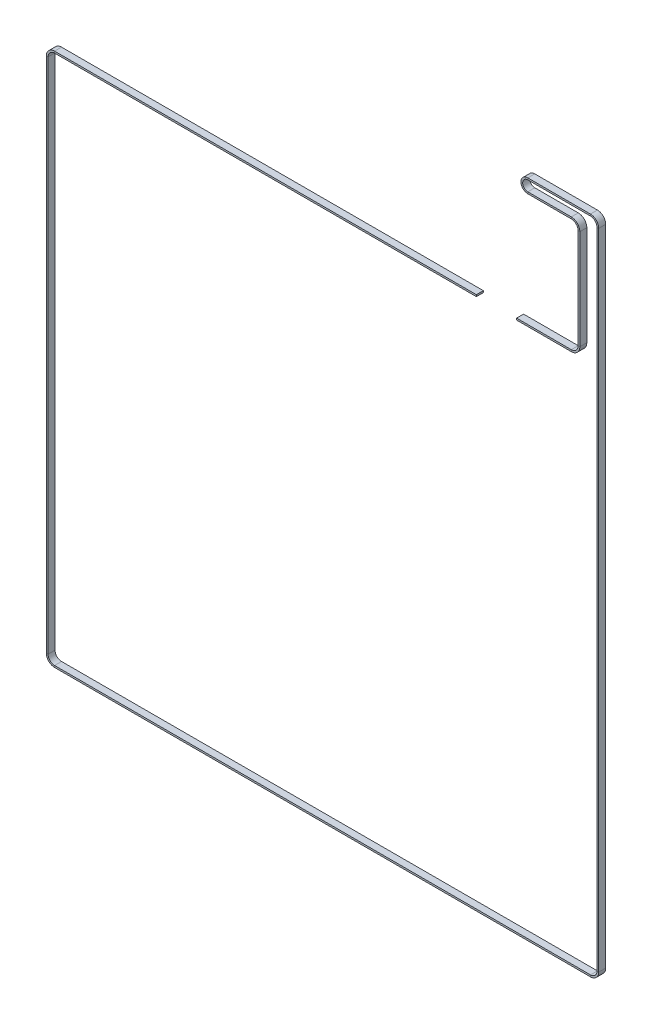
SolidWorks part; units mm, degrees
ref_plane "Front" through (0, 0, 0) normal (0, 0, 1) x (1, 0, 0)
ref_plane "Top" through (0, 0, 0) normal (0, 1, 0) x (1, 0, 0)
ref_plane "Right" through (0, 0, 0) normal (1, 0, 0) x (0, 0, -1)
sketch "Sketch1" plane through (0, 0, 2.2) normal (0, 0, 1) x (1, 0, 0)
  line L0 (377.3122, -142.2854) -> (431.3122, -142.2854)
  line L1 (377.3122, -152.6854) -> (414.8122, -152.6854)
  line L2 (421.4122, -159.2854) -> (421.4122, -245.207)
  line L3 (437.6872, -148.6604) -> (437.6872, -703.9854)
  line L4 (-37.0628, -703.9854) -> (-37.0628, -258.032)
  line L5 (431.3122, -710.3604) -> (-30.6878, -710.3604)
  line L6 (-30.6878, -251.657) -> (332.9622, -251.657)
  line L8 (367.6622, -251.707) -> (367.6622, -255.207) construction
  line L9 (414.8122, -251.807) -> (367.6622, -251.807)
  line L11 (332.9622, -251.707) -> (332.9622, -255.207) construction
  circle A0 centre (414.8122, -159.2854) radius 6.6 construction
  circle A1 centre (431.3122, -148.6604) radius 6.375 construction
  circle A2 centre (377.3122, -147.4854) radius 5.2 construction
  arc A3 (431.3122, -142.2854) -> (437.6872, -148.6604) centre (431.3122, -148.6604) cw
  arc A4 (377.3122, -152.6854) -> (377.3122, -142.2854) centre (377.3122, -147.4854) cw
  arc A5 (414.8122, -152.6854) -> (421.4122, -159.2854) centre (414.8122, -159.2854) cw
  circle A6 centre (-30.6878, -703.9854) radius 6.375 construction
  arc A7 (-30.6878, -710.3604) -> (-37.0628, -703.9854) centre (-30.6878, -703.9854) cw
  circle A8 centre (431.3122, -148.6604) radius 9 construction
  circle A9 centre (414.8122, -159.2854) radius 9 construction
  circle A10 centre (-30.6878, -258.032) radius 6.375 construction
  circle A11 centre (431.3122, -703.9854) radius 6.375 construction
  arc A12 (437.6872, -703.9854) -> (431.3122, -710.3604) centre (431.3122, -703.9854) cw
  arc A13 (-37.0628, -258.032) -> (-30.6878, -251.657) centre (-30.6878, -258.032) cw
  circle A14 centre (414.8122, -245.207) radius 6.6 construction
  arc A15 (421.4122, -245.207) -> (414.8122, -251.807) centre (414.8122, -245.207) cw
  circle A16 centre (414.8122, -245.207) radius 5.9875 construction
  circle A17 centre (-30.6878, -258.032) radius 5.9875 construction
  dimension "D1" = 12.75
ref_plane "Plane1" through (332.9622, -251.657, 2.2) normal (1, 0, 0) x (0, 0, -1)
sketch "Sketch4" plane through (332.9622, -251.657, 2.2) normal (1, 0, 0) x (0, 0, -1)
  line L0 (0, 102.9966) -> (0, -452.3284) construction
  line L1 (3, -0.75) -> (-3, -0.75)
  line L2 (3, -0.75) -> (3, 0.75)
  line L3 (3, 0.75) -> (-3, 0.75)
  line L4 (-3, -0.75) -> (-3, 0.75)
  line L5 (3, -0.75) -> (-3, 0.75) construction
  line L6 (3, 0.75) -> (-3, -0.75) construction
  line L7 (0, 0) -> (0, -12.75) construction
  point P0 (0, 0)
  dimension "D1" = 1.5
  dimension "D2" = 6
sweep "Sweep1" add profiles "Sketch4" path "Sketch1"
